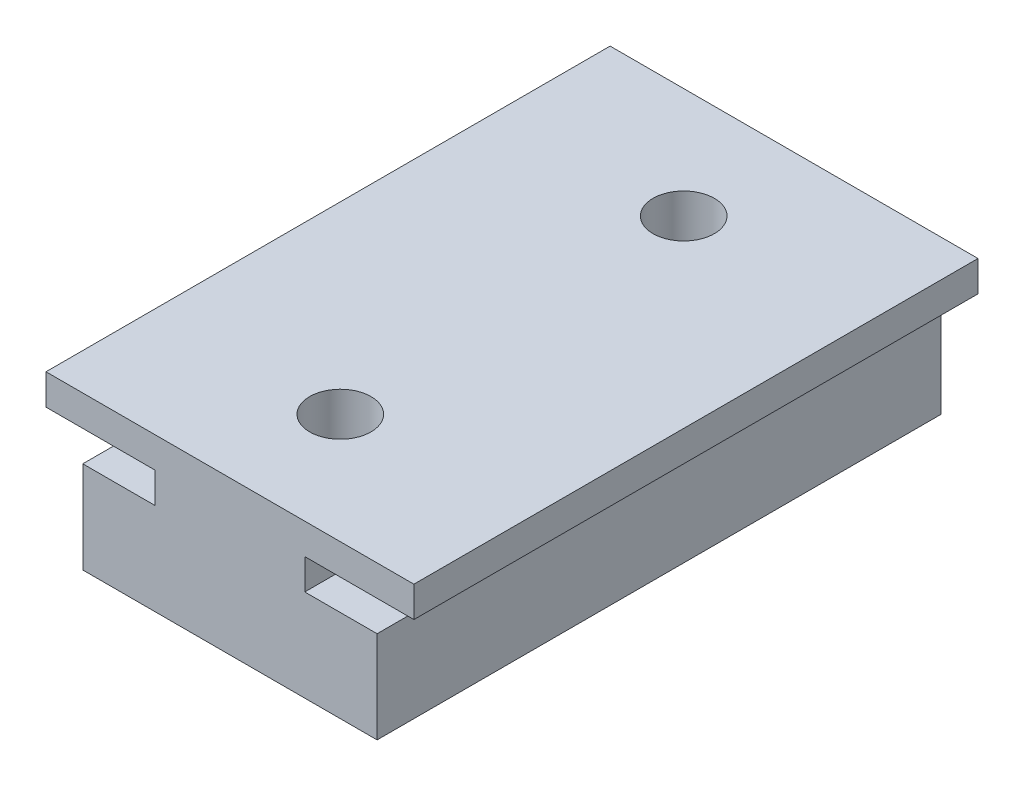
SolidWorks part; units mm, degrees
ref_plane "Front Plane" through (0, 0, 0) normal (0, 0, 1) x (1, 0, 0)
ref_plane "Top Plane" through (0, 0, 0) normal (0, 1, 0) x (1, 0, 0)
ref_plane "Right Plane" through (0, 0, 0) normal (1, 0, 0) x (0, 0, -1)
sketch "Sketch1" plane through (0, 0, 0) normal (0, 0, 1) x (1, 0, 0)
  line L0 (0, 0) -> (0, 32.5433) construction
  line L1 (-15, 12.5) -> (15, 12.5)
  line L2 (15, 12.5) -> (15, 10)
  line L3 (15, 10) -> (6.1, 10)
  line L4 (6.1, 10) -> (6.1, 7.5)
  line L5 (6.1, 7.5) -> (12, 7.5)
  line L6 (12, 7.5) -> (12, 0)
  line L7 (12, 0) -> (-12, 0)
  line L8 (-12, 7.5) -> (-12, 0)
  line L9 (-6.1, 7.5) -> (-12, 7.5)
  line L10 (-6.1, 10) -> (-6.1, 7.5)
  line L11 (-15, 10) -> (-6.1, 10)
  line L12 (-15, 12.5) -> (-15, 10)
  point P16 (0, 12.5)
  dimension "D1" = 15
  dimension "D2" = 12
  dimension "D3" = 7.5
  dimension "D4" = 6.1
  dimension "D5" = 2.5
  dimension "D6" = 12.5
extrude "Boss-Extrude1" add sketch "Sketch1" along normal blind 46
sketch "Sketch2" plane through (0, 12.5, 0) normal (0, 1, 0) x (1, 0, 0)
  line L0 (15, -46) -> (-15, -46) construction
  circle A0 centre (0, -9) radius 2.5
  circle A1 centre (0, -37) radius 2.5
  dimension "D1" = 5
  dimension "D2" = 5
  dimension "D3" = 9
  dimension "D4" = 28
extrude "Cut-Extrude1" cut sketch "Sketch2" against normal through all
